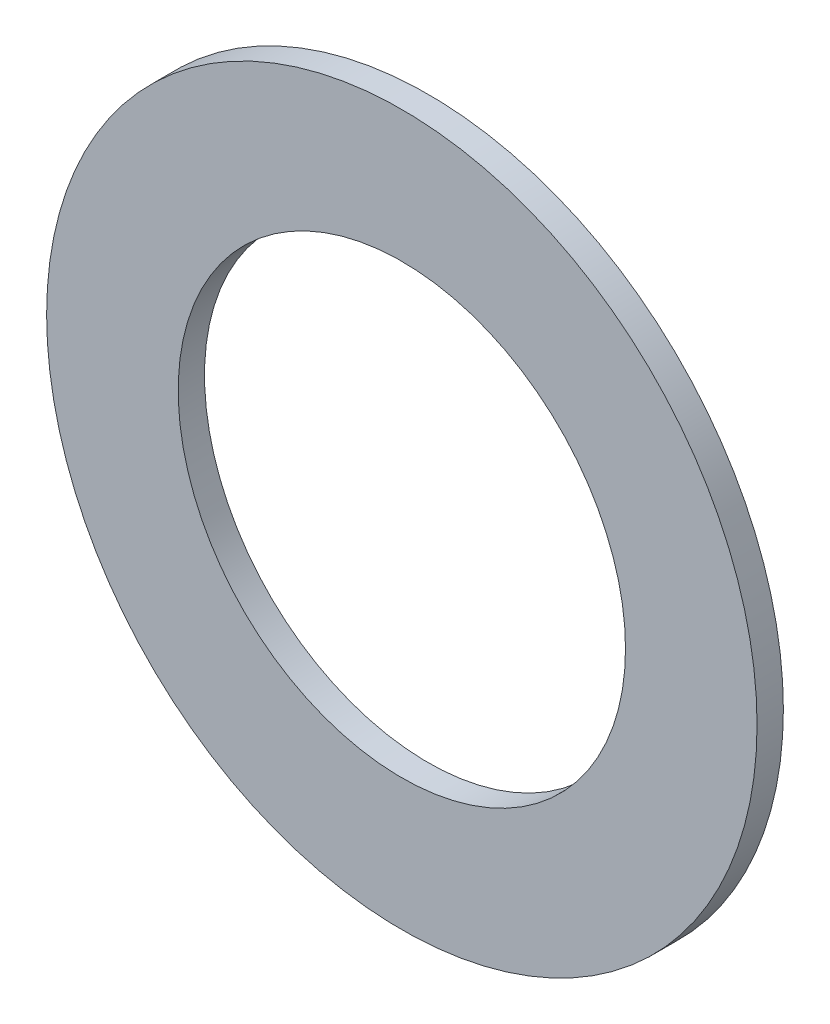
SolidWorks part; units mm, degrees
ref_plane "Front Plane" through (0, 0, 0) normal (0, 0, 1) x (1, 0, 0)
ref_plane "Top Plane" through (0, 0, 0) normal (0, 1, 0) x (1, 0, 0)
ref_plane "Right Plane" through (0, 0, 0) normal (1, 0, 0) x (0, 0, -1)
sketch "Sketch1" plane through (0, 0, 0) normal (0, 0, 1) x (1, 0, 0)
  circle A0 centre (0, 0) radius 8.5
  circle A1 centre (0, 0) radius 13.5
  dimension "D1" = 17
  dimension "D2" = 5
extrude "Boss-Extrude1" add sketch "Sketch1" along normal blind 1
